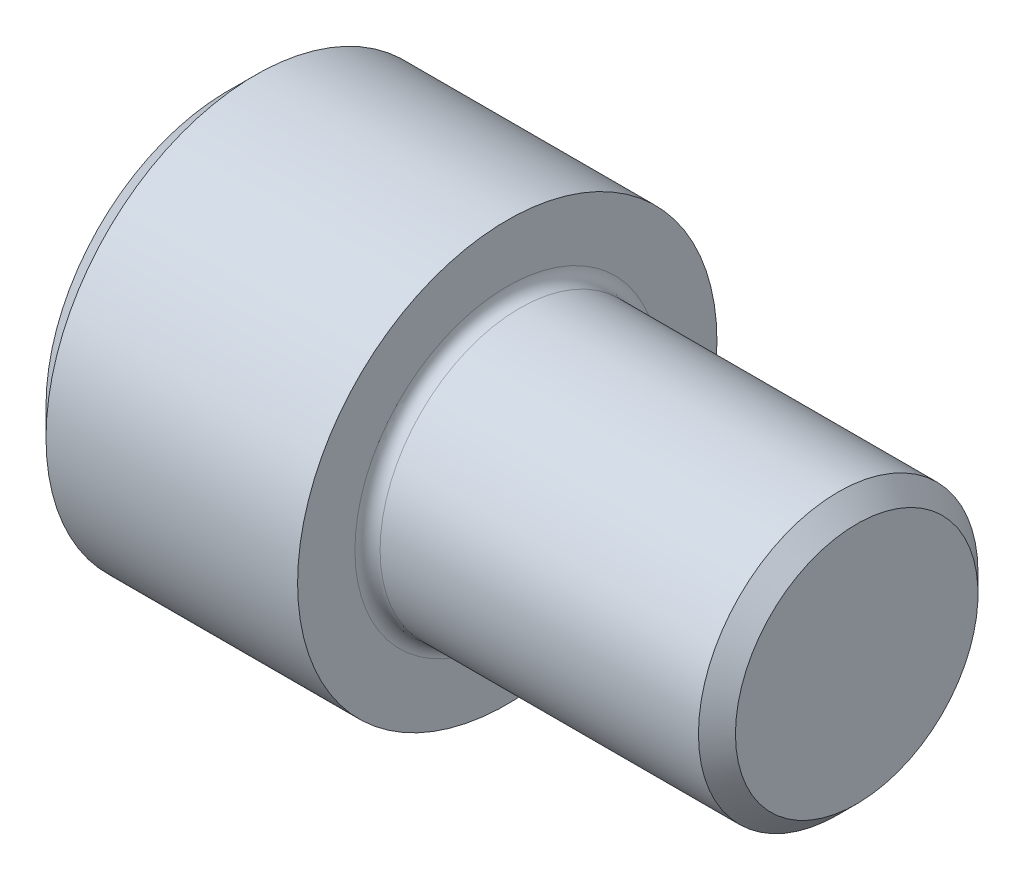
SolidWorks part; units mm, degrees
revolve "Base-Revolve" add sketch "BodySke"
sketch "BodySke" plane through (0, 0, 0) normal (0, 0, 1) x (1, 0, 0)
  line L0 (0, 0) -> (0, 33.02)
  line L1 (5.08, 38.1) -> (50.8, 38.1)
  line L2 (50.8, 38.1) -> (50.8, 25.4)
  line L3 (50.8, 25.4) -> (110.9383, 25.4)
  line L4 (114.3, 22.0383) -> (114.3, 0)
  line L5 (114.3, 0) -> (0, 0)
  line L6 (-31.75, 0) -> (127, 0) construction
  line L7 (0, 33.02) -> (5.08, 38.1)
  line L8 (114.3, 22.0383) -> (110.9383, 25.4)
  line L9 (0, -33.02) -> (5.08, -38.1) construction
  line L10 (114.3, -22.0383) -> (110.9383, -25.4) construction
  line L11 (56.4439, 9.525) -> (56.4439, 3.175) construction
  line L12 (50.8, 9.525) -> (50.8, 3.175) construction
  line L13 (76.2, 9.525) -> (76.2, 3.175) construction
  dimension "Diameter" = 50.8
  dimension "Head_ht" = 50.8
  dimension "Length" = 63.5
  dimension "Body_ch_ang" = 45
  dimension "Head_dia" = 76.2
  dimension "Head_ch_ang" = 45
  dimension "Head_side_ht" = 45.72
  dimension "Minor_dia" = 44.0766
  dimension "Advance" = 5.6439
  dimension "Thread_nom" = 63.5
  dimension "Thread_length" = 38.1
cosmetic thread "ThreadCosmetic" [suppressed]
fillet "Fillet1" radius 2.286 1 edges at (50.8, 0, 25.4)
ref_plane "Plane1" through (0, 0, 0) normal (0, 0, 1) x (1, 0, 0)
ref_plane "Plane2" through (0, 0, 0) normal (0, 1, 0) x (1, 0, 0)
ref_plane "Plane3" through (0, 0, 0) normal (1, 0, 0) x (0, 0, -1)
sketch "Sketch2" plane through (0, 0, 0) normal (0, 0, 1) x (1, 0, 0)
  line L0 (0, 19.05) -> (25.273, 19.05)
  line L1 (25.273, 19.05) -> (36.2715, 0)
  line L2 (-31.75, 0) -> (127, 0) construction
  line L3 (36.2715, 0) -> (0, 0)
  line L4 (0, 0) -> (0, 19.05)
  line L5 (0, 33.02) -> (0, -33.02) construction
  line L6 (0, 0) -> (47.625, 0) construction
  line L7 (50.8, -38.1) -> (50.8, 38.1) construction
  dimension "D1" = 19.05
  dimension "D2" = 60
revolve "Hex-PreBroach" cut sketch "Sketch2" angle 360 about L6
sketch "Sketch3" plane through (0, 0, 0) normal (-1, 0, 0) x (0, 0.5, 0.866)
  line L0 (10.9985, 19.05) -> (-10.9985, 19.05)
  line L1 (-10.9985, 19.05) -> (-21.997, 0)
  line L2 (10.9985, 19.05) -> (21.997, 0)
  line L3 (10.9985, -19.05) -> (21.997, 0)
  line L4 (10.9985, -19.05) -> (-10.9985, -19.05)
  line L5 (-10.9985, -19.05) -> (-21.997, 0)
  dimension "D1" = 19.05
  dimension "D2" = 19.05
  dimension "Hex_size" = 38.1
extrude "Hex" cut sketch "Sketch3" against normal blind 25.273
sketch "Sketch4" plane through (0, 0, 0) normal (-1, 0, 0) x (0, 0, 1)
  line L0 (0, 0) -> (10.1727, 0)
  line L1 (0, 0) -> (6.1484, 3.5498) construction
  line L2 (0, 0) -> (5.0863, 8.8098)
  line L3 (8.4417, 2.1022) -> (9.7612, 2.864)
  line L4 (6.0414, 6.2596) -> (7.3609, 7.0215)
  arc A0 (8.4417, 2.1022) -> (6.0414, 6.2596) centre (0, 0) ccw
  arc A1 (10.1727, 0) -> (9.7612, 2.864) centre (0, 0) ccw
  arc A2 (5.0863, 8.8098) -> (7.3609, 7.0215) centre (0, 0) cw
  dimension "D1" = 30
  dimension "D2" = 60
  dimension "Spline_p_dim" = 4.8006
  dimension "D3" = 2.4003
extrude "Spline" [suppressed] cut sketch "Sketch4" against normal blind 25.273
pattern_circular "CirPattern1" [suppressed] count 6 every 60
sketch "Sketch5" plane through (0, 0, 0) normal (0, 0, 1) x (1, 0, 0)
  line L0 (-31.75, 0) -> (127, 0) construction
  line L2 (0, 33.02) -> (0, -33.02) construction
  circle A0 centre (11.684, 0) radius 1.524
  dimension "Drilled_hole_dia" = 3.048
  dimension "Drilled_hole_loc" = 11.684
extrude "Hole" [suppressed] cut sketch "Sketch5" against normal through all and the other way through all
pattern_circular "Drilled-4" [suppressed] count 2 every 60
pattern_circular "Drilled-6" [suppressed] count 3 every 60
sketch "ThdSchSke" plane through (0, 0, 0) normal (0, 0, 1) x (1, 0, 0)
  line L0 (56.4439, -22.0383) -> (54.09, -25.4)
  line L1 (56.4439, -22.0383) -> (58.7978, -25.4)
  line L2 (58.7978, -25.4) -> (58.7978, -31.75)
  line L3 (-3.175, 0) -> (5.1513, 0) construction
  line L5 (58.7978, -31.75) -> (54.09, -31.75)
  line L6 (54.09, -31.75) -> (54.09, -25.4)
  line L7 (0, 33.02) -> (0, -33.02) construction
  dimension "Diameter" = 50.8
revolve "ThreadSchematic" [suppressed] cut sketch "ThdSchSke" angle 360 about L3
pattern_linear "ThdSchPat" [suppressed]
equation "\"D2@Sketch3\" = \"Hex_size@Sketch3\" / 2"
equation "\"D1@Sketch3\" = \"Hex_size@Sketch3\" / 2"
equation "\"D1@Sketch2\" = \"Hex_size@Sketch3\" / 2"
equation "\"D3@Sketch4\" = \"Spline_p_dim@Sketch4\" / 2"
equation "\"Thread_minor@ThreadCosmetic\"  =  \"Minor_dia@BodySke\""
equation "\"D2@CirPattern1\" = 360 / \"Num_teeth@CirPattern1\""
equation "\"Wall_thickness@Sketch2\" = \"Head_ht@BodySke\" - \"Key_eng@Hex\""
equation "\"Thread_length@ThreadCosmetic\" = ((sgn( (\"Length@BodySke\" - \"Advance@BodySke\" ) - \"Thread_nom@BodySke\" )-1)*( (\"Length@BodySke\" - \"Advance@BodySke\" ) - \"Thread_nom@BodySke\" ))/-2+ \"Thread_nom@BodySke\""
equation "\"Thread_minor@ThdSchSke\" = \"Minor_dia@BodySke\""
equation "\"Diameter@ThdSchSke\" = \"Diameter@BodySke\""
equation "\"Overcut@ThdSchSke\" = \"Diameter@BodySke\" * 1.25"
equation "\"Start@ThdSchSke\" = \"Head_ht@BodySke\" + \"Length@BodySke\" - \"Thread_length@ThreadCosmetic\"  '---Non-countersunk---"
equation "\"Num_threads@ThdSchPat\" = int( \"Thread_length@ThreadCosmetic\" / \"Advance@BodySke\" + 0.999 )  + 1"
equation "\"Advance@ThdSchPat\" = \"Thread_length@ThreadCosmetic\" /  (\"Num_threads@ThdSchPat\" - 1) 'relax it"
equation "\"Num_threads@ThdSchPat\" = \"Num_threads@ThdSchPat\" - sgn( \"Num_threads@ThdSchPat\" - 1) '---chamfered tips only---"
